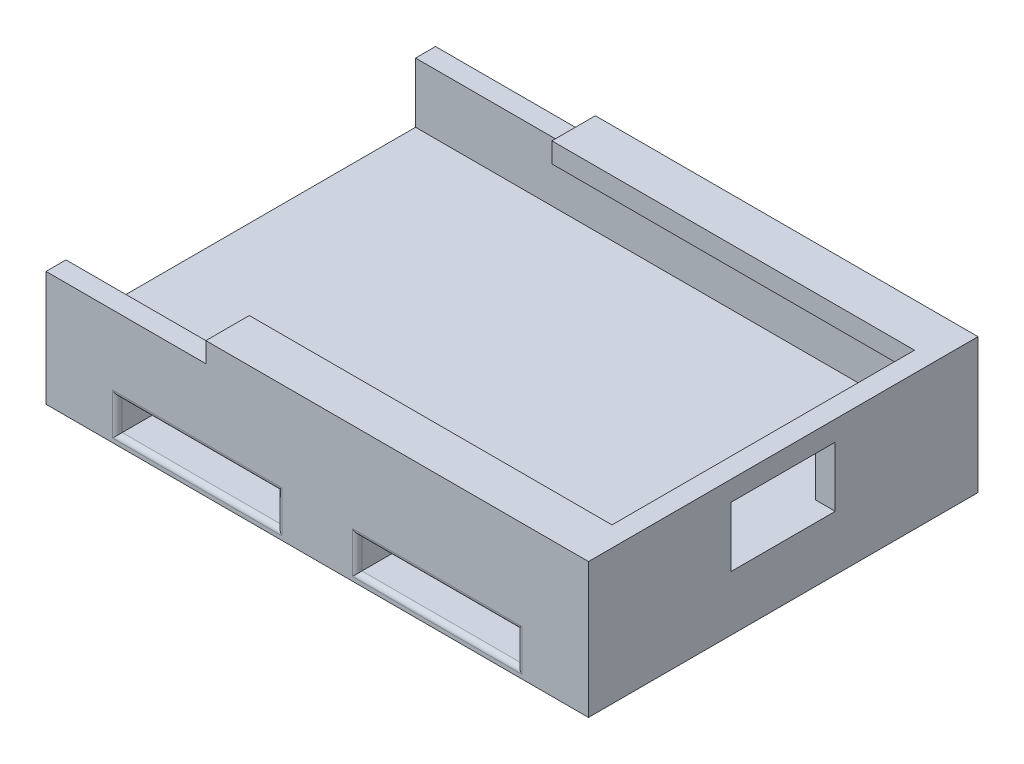
SolidWorks part; units mm, degrees
ref_plane "Front Plane" through (0, 0, 0) normal (0, 0, 1) x (1, 0, 0)
ref_plane "Top Plane" through (0, 0, 0) normal (0, 1, 0) x (1, 0, 0)
ref_plane "Right Plane" through (0, 0, 0) normal (1, 0, 0) x (0, 0, -1)
sketch "Sketch1" plane through (0, 0, 0) normal (1, 0, 0) x (0, 0, -1)
  line L0 (-3.4975, 0) -> (3.9817, 0) construction
  line L1 (-27.7749, 9.525) -> (-24.0411, 9.525)
  line L2 (0, 6.3447) -> (0, -3.1803) construction
  line L7 (-27.7749, 0) -> (27.7749, 0)
  line L8 (-27.7749, 0) -> (-27.7749, 9.525)
  line L9 (27.7749, 0) -> (27.7749, 9.525)
  line L10 (27.7749, 9.525) -> (24.0411, 9.525)
  line L11 (30.9499, 12.7) -> (24.0411, 12.7)
  line L12 (30.9499, -3.175) -> (30.9499, 12.7)
  line L14 (-30.9499, -3.175) -> (-30.9499, 12.7)
  line L15 (-30.9499, 12.7) -> (-24.0411, 12.7)
  line L16 (-24.0411, 12.7) -> (-24.0411, 9.525)
  line L17 (24.0411, 12.7) -> (24.0411, 9.525)
  line L18 (-30.9499, -8.763) -> (30.9499, -8.763)
  line L19 (-30.9499, -3.175) -> (-30.9499, -8.763)
  line L20 (30.9499, -3.175) -> (30.9499, -8.763)
  line L22 (-30.9499, -3.175) -> (30.9499, -3.175) construction
  point P3 (0, 0)
  dimension "D1" = 3.7338
  dimension "D2" = 3.175
  dimension "D4" = 9.525
extrude "Boss-Extrude1" add sketch "Sketch1" along normal blind 83.0326
sketch "Sketch2" plane through (83.0326, 0, 0) normal (1, 0, 0) x (0, 0, -1)
  line L0 (-30.9499, 12.7) -> (30.9499, 12.7)
  line L1 (30.9499, 12.7) -> (30.9499, -8.763)
  line L2 (30.9499, -8.763) -> (-30.9499, -8.763)
  line L3 (-30.9499, -8.763) -> (-30.9499, 12.7)
extrude "Boss-Extrude2" add sketch "Sketch2" along normal blind 3.175
sketch "Sketch3" plane through (0, 0, 30.9499) normal (0, 0, 1) x (1, 0, 0)
  line L0 (0, -4.8159) -> (86.2076, -4.8159) construction
  line L1 (0, 12.7) -> (0, -8.763) construction
  line L2 (86.2076, 12.7) -> (86.2076, -8.763) construction
  line L3 (43.1038, 12.7) -> (43.1038, -8.763) construction
  line L4 (36.7538, -7.3559) -> (11.3538, -7.3559)
  line L5 (36.7538, -7.3559) -> (36.7538, -2.2759)
  line L6 (36.7538, -2.2759) -> (11.3538, -2.2759)
  line L7 (11.3538, -7.3559) -> (11.3538, -2.2759)
  line L8 (36.7538, -7.3559) -> (11.3538, -2.2759) construction
  line L9 (36.7538, -2.2759) -> (11.3538, -7.3559) construction
  line L10 (86.2076, 12.7) -> (0, 12.7) construction
  line L11 (86.2076, -8.763) -> (0, -8.763) construction
  line L12 (74.8538, -7.3559) -> (74.8538, -2.2759)
  line L13 (49.4538, -2.2759) -> (74.8538, -2.2759)
  line L14 (49.4538, -7.3559) -> (49.4538, -2.2759)
  line L15 (49.4538, -7.3559) -> (74.8538, -7.3559)
  line L16 (24.0538, -2.2759) -> (24.0538, -7.3559) construction
  point P6 (24.0538, -4.8159)
  dimension "D1" = 25.4
  dimension "D2" = 19.05
  dimension "D3" = 5.08
extrude "Cut-Extrude1" cut sketch "Sketch3" against normal through all
fillet "Fillet1" radius 0.762 4 edges at (62.1538, -7.3559, -30.9499) (24.0538, -7.3559, -30.9499) (62.1538, -7.3559, 30.9499) (24.0538, -7.3559, 30.9499)
fillet "Fillet2" radius 0.762 6 edges at (11.3538, -5.1969, -30.9499) (24.0538, -2.2759, -30.9499) (36.7538, -5.1969, -30.9499) (49.4538, -5.1969, -30.9499) (62.1538, -2.2759, -30.9499) (74.8538, -5.1969, -30.9499)
fillet "Fillet3" radius 0.762 6 edges at (74.8538, -5.1969, 30.9499) (62.1538, -2.2759, 30.9499) (49.4538, -5.1969, 30.9499) (11.3538, -5.1969, 30.9499) (24.0538, -2.2759, 30.9499) (36.7538, -5.1969, 30.9499)
sketch "Sketch5" plane through (83.0326, 0, 0) normal (-1, 0, 0) x (0, 0, 1)
  line L0 (-27.7749, 4.7625) -> (27.7749, 4.7625) construction
  line L1 (-27.7749, 9.525) -> (-27.7749, 0) construction
  line L2 (27.7749, 0) -> (27.7749, 9.525) construction
  line L4 (8.265, 0) -> (-8.265, 0)
  line L5 (8.265, 0) -> (8.265, 9.525)
  line L6 (8.265, 9.525) -> (-8.265, 9.525)
  line L7 (-8.265, 0) -> (-8.265, 9.525)
  line L8 (8.265, 0) -> (-8.265, 9.525) construction
  line L9 (8.265, 9.525) -> (-8.265, 0) construction
  point P6 (0, 4.7625)
  dimension "D1" = 9.525
extrude "Cut-Extrude2" cut sketch "Sketch5" against normal through all
sketch "Sketch40" plane through (0, 0, 0) normal (-1, 0, 0) x (0, 0, 1)
  line L0 (27.7749, 0) -> (30.9499, 0) construction
  line L1 (-27.7749, 0) -> (27.7749, 0) construction
  line L2 (8.265, 0) -> (27.7749, 0) construction
  line L3 (30.9499, 12.7) -> (30.9499, -8.763) construction
sketch "Sketch42" plane through (0, 12.7, 0) normal (0, 1, 0) x (1, 0, 0)
  line L0 (0, 30.9499) -> (0, 24.0411)
  line L3 (0, 24.0411) -> (25.4, 24.0411)
  line L4 (83.0326, 24.0411) -> (0, 24.0411) construction
  line L5 (25.4, 24.0411) -> (25.4, 30.9499)
  line L6 (86.2076, 30.9499) -> (0, 30.9499) construction
  line L7 (25.4, 30.9499) -> (0, 30.9499)
  line L8 (0, 0) -> (24.1677, 0) construction
  line L9 (0, -30.9499) -> (0, -24.0411)
  line L10 (25.4, -30.9499) -> (0, -30.9499)
  line L11 (25.4, -24.0411) -> (25.4, -30.9499)
  line L12 (0, -24.0411) -> (25.4, -24.0411)
  point P13 (0, 27.4955)
  point P14 (0, -27.4955)
  dimension "D1" = 25.4
extrude "Cut-Extrude3" cut sketch "Sketch42" against normal blind 3.175
